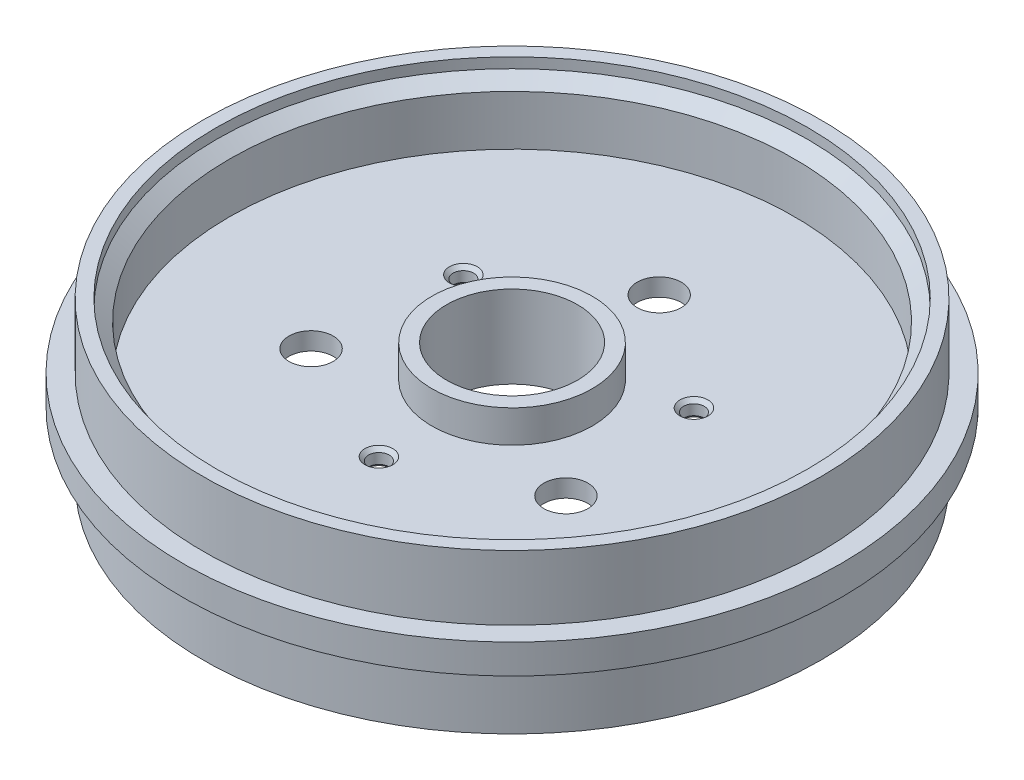
SolidWorks part; units mm, degrees
ref_plane "Front Plane" through (0, 0, 0) normal (0, 0, 1) x (1, 0, 0)
ref_plane "Top Plane" through (0, 0, 0) normal (0, 1, 0) x (1, 0, 0)
ref_plane "Right Plane" through (0, 0, 0) normal (1, 0, 0) x (0, 0, -1)
sketch "Sketch1" plane through (0, 0, 0) normal (0, 0, 1) x (1, 0, 0)
  line L0 (0, 0) -> (4.45, 0) construction
  line L1 (4.45, 0) -> (4.45, 2.8)
  line L2 (4.45, 2.8) -> (5.45, 2.8)
  line L3 (5.45, 2.8) -> (5.45, 0.6)
  line L4 (5.45, 0.6) -> (19.2, 0.6)
  line L5 (19.2, 0.6) -> (19.2, 4)
  line L7 (20.1, 5.4) -> (21, 5.4)
  line L8 (21, 5.4) -> (21, 1)
  line L9 (21, 1) -> (22.4, 1)
  line L10 (22.4, 1) -> (22.4, 0)
  line L11 (22.4, 0) -> (4.45, 0)
  line L12 (20.1, 5.4) -> (20.1, 4.7)
  line L13 (20.1, 4.7) -> (19.2, 4)
  line L14 (19.2, 4) -> (20.1, 4) construction
  line L15 (20.1, 4) -> (20.1, 4.7) construction
  line L16 (0, -5.4) -> (0, 5.4) construction
  point P17 (0, 0)
  dimension "D1" = 22.4
  dimension "D2" = 4.45
  dimension "D3" = 1
  dimension "D4" = 4.8
  dimension "D5" = 2.8
  dimension "D6" = 1.8
  dimension "D7" = 1.4
  dimension "D8" = 1
  dimension "D9" = 5.4
  dimension "D10" = 0.9
  dimension "D11" = 0.7
revolve "Revolve1" add sketch "Sketch1" angle 360 about L16
mirror "Mirror1" about plane through (22.4, 0, 0) normal (0, -1, 0) of "Revolve1"
sketch "Sketch3" plane through (0, 0.6, 0) normal (0, 1, 0) x (1, 0, 0)
  line L1 (0, 10) -> (-8.6603, -5) construction
  line L2 (-8.6603, -5) -> (8.6603, -5) construction
  line L3 (8.6603, -5) -> (0, 10) construction
  line L4 (0, -9.05) -> (7.8375, 4.525) construction
  line L5 (7.8375, 4.525) -> (-7.8375, 4.525) construction
  line L6 (-7.8375, 4.525) -> (0, -9.05) construction
  circle A0 centre (0, 10) radius 1.5
  circle A1 centre (0, 0) radius 5 construction
  circle A2 centre (-8.6603, -5) radius 1.5
  circle A3 centre (8.6603, -5) radius 1.5
  circle A4 centre (0, 0) radius 4.525 construction
  circle A5 centre (-7.8375, 4.525) radius 0.7
  circle A6 centre (7.8375, 4.525) radius 0.7
  circle A7 centre (0, -9.05) radius 0.7
  circle A8 centre (0, 0) radius 10 construction
  circle A9 centre (0, -9.05) radius 0.95 construction
  point P16 (0, -10)
  point P19 (0, -9.75)
  dimension "D2" = 3
  dimension "D3" = 1.9
  dimension "D4" = 1.4
  dimension "D1" = 10
extrude "Cut-Extrude1" cut sketch "Sketch3" against normal up to surface (1.2 mm away) up to face at (5.45, -0.6, 0)
sketch "Sketch4" plane through (0, 0.6, 0) normal (0, 1, 0) x (1, 0, 0)
  circle A0 centre (0, -9.05) radius 0.95
  circle A1 centre (7.8375, 4.525) radius 0.95
  circle A2 centre (-7.8375, 4.525) radius 0.95
  dimension "D1" = 1.9
extrude "Cut-Extrude2" cut sketch "Sketch4" against normal blind 1 draft 45
sketch "Sketch5" plane through (0, -0.6, 0) normal (0, -1, 0) x (1, 0, 0)
  circle A0 centre (7.8375, -4.525) radius 0.95
  circle A1 centre (0, 9.05) radius 0.95
  circle A2 centre (-7.8375, -4.525) radius 0.95
  circle A3 centre (7.8375, -4.525) radius 0.95 construction
extrude "Cut-Extrude3" cut sketch "Sketch5" against normal blind 1 draft 45
